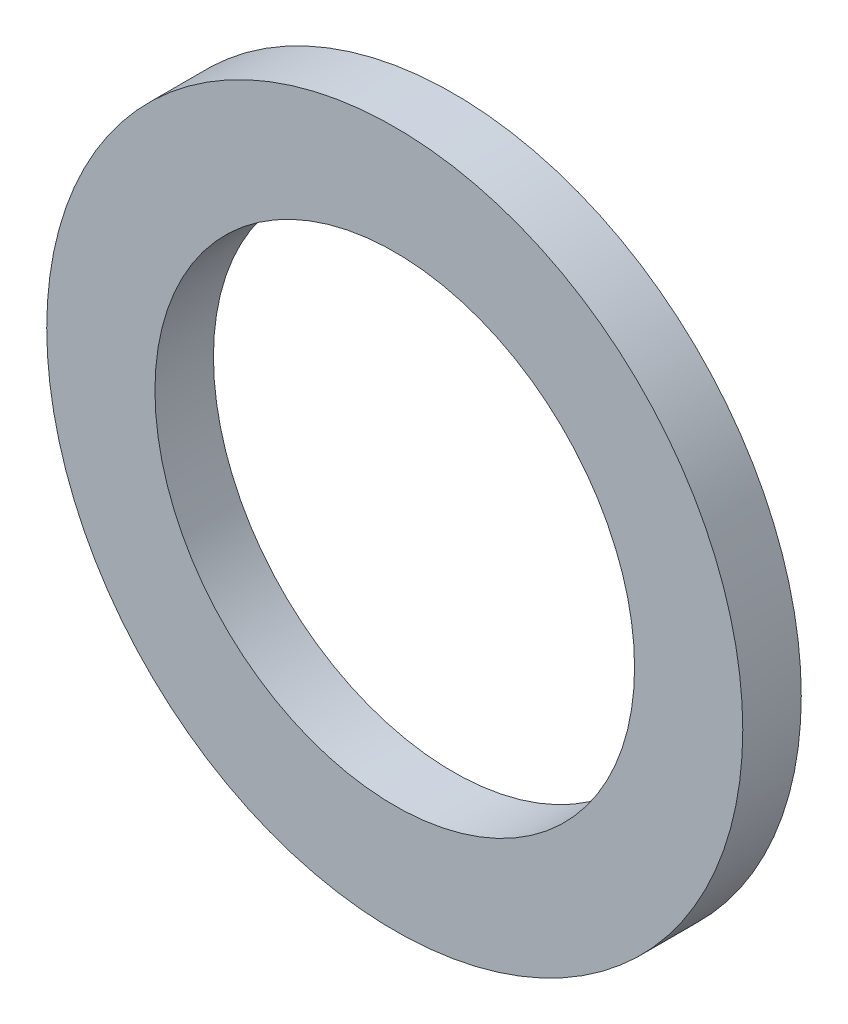
SolidWorks part; units mm, degrees
ref_plane "Front Plane" through (0, 0, 0) normal (0, 0, 1) x (1, 0, 0)
ref_plane "Top Plane" through (0, 0, 0) normal (0, 1, 0) x (1, 0, 0)
ref_plane "Right Plane" through (0, 0, 0) normal (1, 0, 0) x (0, 0, -1)
sketch "Sketch1" plane through (0, 0, 0) normal (0, 0, 1) x (1, 0, 0)
  circle A0 centre (0, 0) radius 4.1
  circle A1 centre (0, 0) radius 5.95
  dimension "ID" = 8.2
  dimension "OD" = 11.9
sketch "Sketch2" plane through (0, 0, 0) normal (1, 0, 0) x (0, 0, -1)
  line L0 (0.5, 0) -> (-0.5, 0)
  point P4 (0, 0)
  dimension "Thickness Avg" = 1
sketch "Sketch3" plane through (0, 0, 0) normal (0, 0, 1) x (1, 0, 0)
  circle A0 centre (0, 0) radius 5.95 construction
  circle A1 centre (0, 0) radius 5.95
  circle A2 centre (0, 0) radius 4.1 construction
  circle A3 centre (0, 0) radius 4.1
extrude "Boss-Extrude1" add sketch "Sketch3" along normal mid plane 1
equation "\"D1@Boss-Extrude1\"=\"Thickness Avg@Sketch2\""
